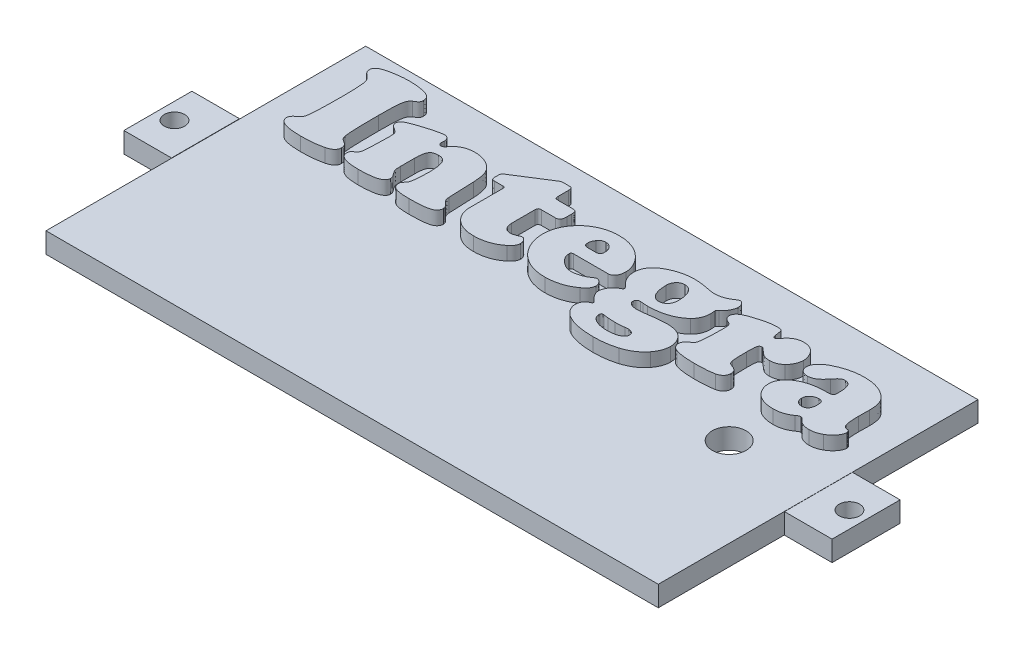
SolidWorks part; units mm, degrees
ref_plane "Alzado" through (0, 0, 0) normal (0, 0, 1) x (1, 0, 0)
ref_plane "Planta" through (0, 0, 0) normal (0, 1, 0) x (1, 0, 0)
ref_plane "Vista lateral" through (0, 0, 0) normal (1, 0, 0) x (0, 0, -1)
sketch "Croquis1" plane through (0, 0, 0) normal (0, 1, 0) x (1, 0, 0)
  line L1 (-45, 23.5) -> (45, 23.5)
  line L2 (-45, 23.5) -> (-45, -23.5)
  line L3 (-45, -23.5) -> (45, -23.5)
  line L4 (45, 23.5) -> (45, -23.5)
  line L5 (-45, 23.5) -> (45, -23.5) construction
  line L6 (-45, -23.5) -> (45, 23.5) construction
  line L7 (-52.0435, 4.9923) -> (-45.0435, 4.9923)
  line L8 (-52.0435, 4.9923) -> (-52.0435, -5.0077)
  line L9 (-52.0435, -5.0077) -> (-45.0435, -5.0077)
  line L10 (-45.0435, 4.9923) -> (-45.0435, -5.0077)
  line L13 (45.0247, 5.0242) -> (52.0247, 5.0242)
  line L14 (45.0247, 5.0242) -> (45.0247, -4.9758)
  line L15 (45.0247, -4.9758) -> (52.0247, -4.9758)
  line L16 (52.0247, 5.0242) -> (52.0247, -4.9758)
  point P0 (0, 0)
extrude "Saliente-Extruir1" add sketch "Croquis1" along normal blind 3
sketch "Croquis2" plane through (0, 3, 0) normal (0, 1, 0) x (1, 0, 0)
  circle A0 centre (31.9213, 0.003) radius 2.5
extrude "Cortar-Extruir1" cut sketch "Croquis2" against normal blind 3
sketch "Croquis3" plane through (0, 3, 0) normal (0, 1, 0) x (1, 0, 0)
  text T0 "Integra" font "Cooper Black" height 15
extrude "Saliente-Extruir2" add sketch "Croquis3" along normal blind 2
sketch "Croquis4" plane through (0, 3, 0) normal (0, 1, 0) x (1, 0, 0)
  circle A0 centre (-49.6163, 0) radius 1.5
  dimension "D1" = 3
extrude "Cortar-Extruir2" cut sketch "Croquis4" against normal blind 3
sketch "Croquis5" plane through (0, 3, 0) normal (0, 1, 0) x (1, 0, 0)
  circle A0 centre (49.5975, 0) radius 1.5
extrude "Cortar-Extruir3" cut sketch "Croquis5" against normal blind 3
